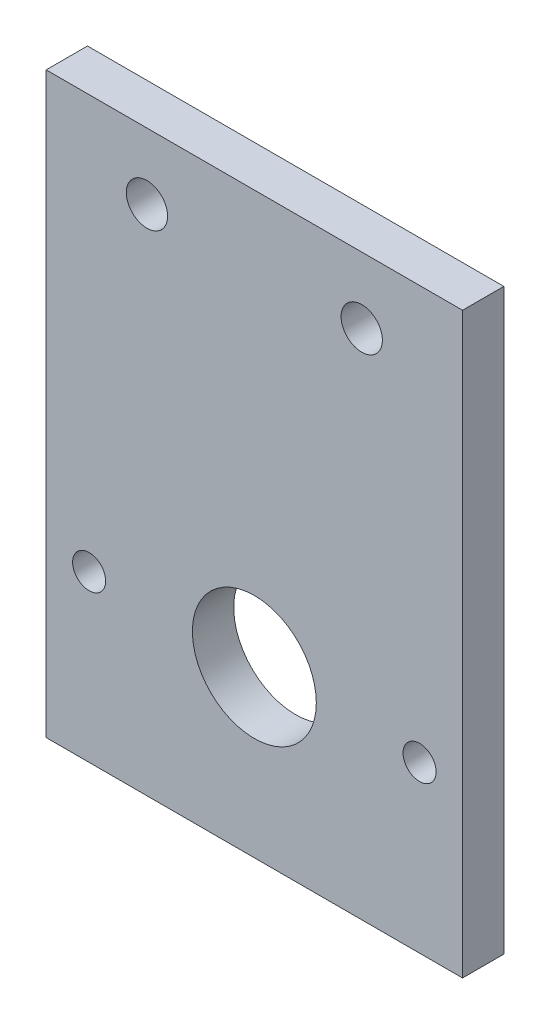
SolidWorks part; units mm, degrees
material "1060 Alloy"
ref_plane "Front Plane" through (0, 0, 0) normal (0, 0, 1) x (1, 0, 0)
ref_plane "Top Plane" through (0, 0, 0) normal (0, 1, 0) x (1, 0, 0)
ref_plane "Right Plane" through (0, 0, 0) normal (1, 0, 0) x (0, 0, -1)
sketch "Sketch1" plane through (0, 0, 0) normal (0, 0, 1) x (1, 0, 0)
  line L1 (-32.004, -44.45) -> (32.004, -44.45)
  line L2 (-32.004, -44.45) -> (-32.004, 44.45)
  line L3 (-32.004, 44.45) -> (32.004, 44.45)
  line L4 (32.004, -44.45) -> (32.004, 44.45)
  line L5 (-32.004, -44.45) -> (32.004, 44.45) construction
  line L6 (-32.004, 44.45) -> (32.004, -44.45) construction
  point P0 (0, 0)
  dimension "D1" = 64.008
  dimension "D2" = 88.9
extrude "Extrude1" add sketch "Sketch1" along normal blind 6.35
sketch "Sketch2" plane through (0, 0, 6.35) normal (0, 0, 1) x (1, 0, 0)
  line L0 (0, 0) -> (0, -69.2265) construction
  line L1 (-32.004, -44.45) -> (32.004, -44.45) construction
  circle A0 centre (-25.4, -19.05) radius 2.54
  circle A1 centre (25.4, -19.05) radius 2.54
  dimension "D1" = 5.08
  dimension "D2" = 50.8
  dimension "D3" = 25.4
extrude "Extrude2" cut sketch "Sketch2" against normal through all
sketch "Sketch3" plane through (0, 0, 6.35) normal (0, 0, 1) x (1, 0, 0)
  line L1 (25.4, -19.05) -> (-25.4, -19.05) construction
  circle A0 centre (0, -19.05) radius 9.525
  dimension "D1" = 19.05
extrude "Extrude4" cut sketch "Sketch3" against normal through all
sketch "Sketch4" plane through (0, 0, 6.35) normal (0, 0, 1) x (1, 0, 0)
  line L0 (0, 0) -> (0, 64.1985) construction
  line L1 (32.004, 44.45) -> (-32.004, 44.45) construction
  circle A0 centre (-16.51, 34.29) radius 3.175
  circle A1 centre (16.51, 34.29) radius 3.175
  dimension "D1" = 6.35
  dimension "D3" = 33.02
  dimension "D2" = 10.16
extrude "Extrude5" cut sketch "Sketch4" against normal through all
